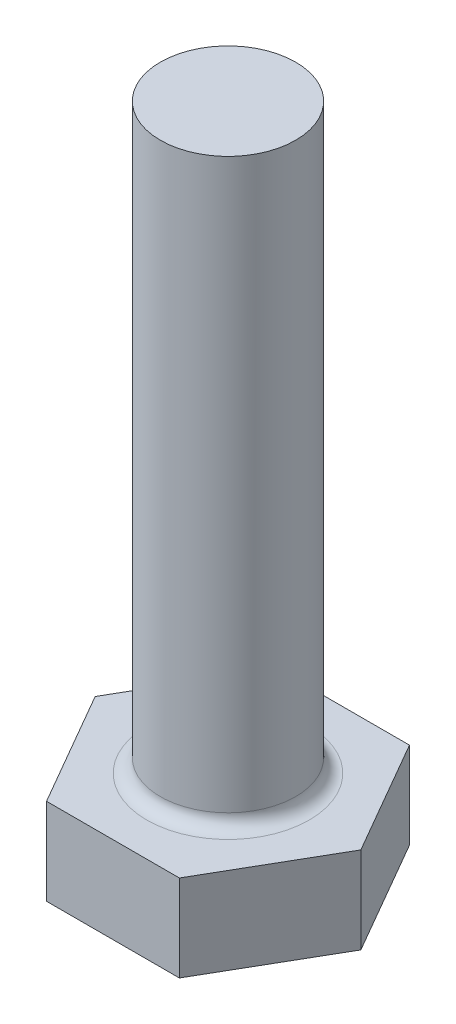
SolidWorks part; units mm, degrees
ref_plane "Front Plane" through (0, 0, 0) normal (0, 0, 1) x (1, 0, 0)
ref_plane "Top Plane" through (0, 0, 0) normal (0, 1, 0) x (1, 0, 0)
ref_plane "Right Plane" through (0, 0, 0) normal (1, 0, 0) x (0, 0, -1)
sketch "Sketch1" plane through (0, 0, 0) normal (0, 1, 0) x (1, 0, 0)
  circle A0 centre (0, 0) radius 5
  dimension "D1" = 10
extrude "Boss-Extrude1" add sketch "Sketch1" along normal blind 43
sketch "Sketch2" plane through (0, 0, 0) normal (0, -1, 0) x (1, 0, 0)
  line L1 (4.9075, 8.5) -> (-4.9075, 8.5)
  line L2 (-4.9075, 8.5) -> (-9.815, 0)
  line L3 (-9.815, 0) -> (-4.9075, -8.5)
  line L4 (-4.9075, -8.5) -> (4.9075, -8.5)
  line L5 (4.9075, -8.5) -> (9.815, 0)
  line L6 (9.815, 0) -> (4.9075, 8.5)
  circle A0 centre (0, 0) radius 8.5 construction
  dimension "D1" = 17
extrude "Boss-Extrude2" add sketch "Sketch2" along normal blind 6.4
fillet "Fillet1" radius 1 1 edges at (0, 0, 5)
sketch "Sketch3" plane through (0, -6.4, 0) normal (0, -1, 0) x (1, 0, 0)
  line L0 (10.0459, 0) -> (5.0229, 8.7)
  line L1 (5.0229, 8.7) -> (-5.0229, 8.7)
  line L2 (-5.0229, 8.7) -> (-10.0459, 0)
  line L3 (-10.0459, 0) -> (-5.0229, -8.7)
  line L4 (-5.0229, -8.7) -> (5.0229, -8.7)
  line L5 (5.0229, -8.7) -> (10.0459, 0)
  line L6 (9.815, 0) -> (4.9075, 8.5)
  line L7 (4.9075, 8.5) -> (-4.9075, 8.5)
  line L8 (-4.9075, 8.5) -> (-9.815, 0)
  line L9 (-9.815, 0) -> (-4.9075, -8.5)
  line L10 (-4.9075, -8.5) -> (4.9075, -8.5)
  line L11 (4.9075, -8.5) -> (9.815, 0)
  line L12 (9.815, 0) -> (4.9075, 8.5)
  line L13 (4.9075, 8.5) -> (-4.9075, 8.5)
  line L14 (-4.9075, 8.5) -> (-9.815, 0)
  line L15 (-9.815, 0) -> (-4.9075, -8.5)
  line L16 (-4.9075, -8.5) -> (4.9075, -8.5)
  line L17 (4.9075, -8.5) -> (9.815, 0)
  circle A1 centre (0, 0) radius 10.0459 construction
  circle A2 centre (0, 0) radius 12.0459
  dimension "D1" = 0
  dimension "D2" = 0.2
  dimension "D3" = 2
